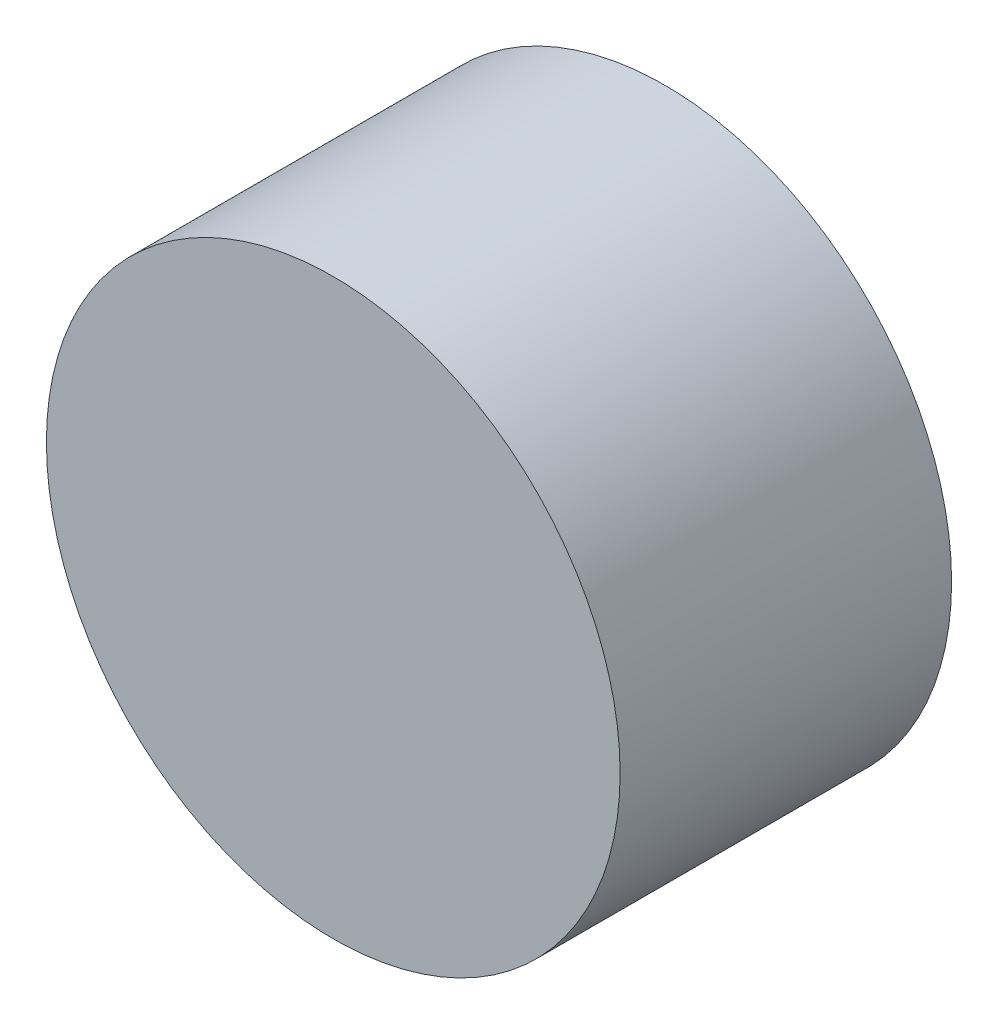
SolidWorks part; units mm, degrees
ref_plane "前视基准面" through (0, 0, 0) normal (0, 0, 1) x (1, 0, 0)
ref_plane "上视基准面" through (0, 0, 0) normal (0, 1, 0) x (1, 0, 0)
ref_plane "右视基准面" through (0, 0, 0) normal (1, 0, 0) x (0, 0, -1)
other "Configuration Table"
sketch "草图1" plane through (0, 0, 0) normal (0, 0, 1) x (1, 0, 0)
  circle A0 centre (0, 0) radius 225
extrude "凸台-拉伸1" add sketch "草图1" along normal blind 260
